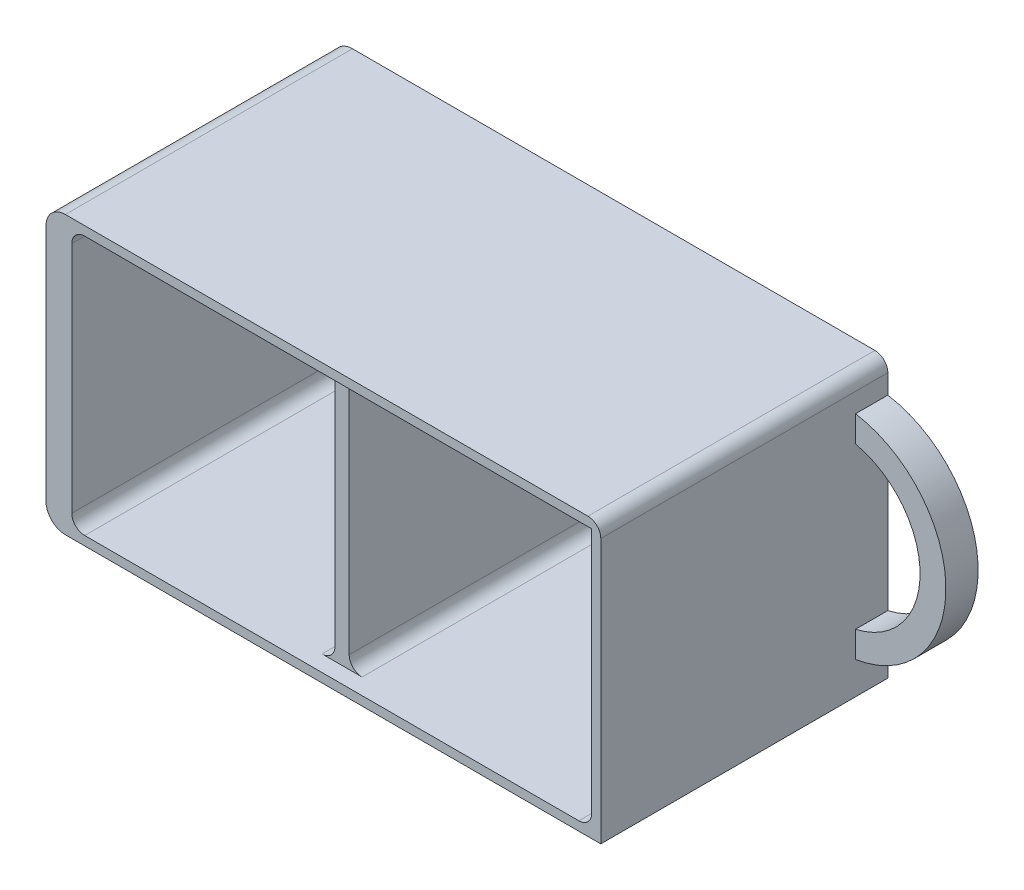
SolidWorks part; units mm, degrees
ref_plane "Спереди" through (0, 0, 0) normal (0, 0, 1) x (1, 0, 0)
ref_plane "Сверху" through (0, 0, 0) normal (0, 1, 0) x (1, 0, 0)
ref_plane "Справа" through (0, 0, 0) normal (1, 0, 0) x (0, 0, -1)
ref_plane "Плоскость4" through (0, 0, 22.25) normal (0, 0, 1) x (1, 0, 0)
sketch "Эскиз1" plane through (0, 0, 22.25) normal (0, 0, 1) x (1, 0, 0)
  line L0 (90, -21.5) -> (90, 21.5)
  line L1 (90, 21.5) -> (4, 21.5)
  line L2 (4, 21.5) -> (4, -21.5)
  line L3 (4, -21.5) -> (90, -21.5)
extrude "Бобышка-Вытянуть1" add sketch "Эскиз1" against normal blind 39.5
sketch "Эскиз2" plane through (0, 0, -17.25) normal (0, 0, -1) x (-1, 0, 0)
  line L0 (-90, -21.5) -> (-90, -16.5)
  line L1 (-90, 16.5) -> (-90, 21.5)
  line L2 (-90, 21.5) -> (-4, 21.5)
  line L3 (-4, 21.5) -> (-4, -21.5)
  line L4 (-4, -21.5) -> (-90, -21.5)
  line L5 (-90, -12.4284) -> (-90, 12.4284)
  arc A0 (-90, -16.5) -> (-90, 16.5) centre (-87.2768, 0) cw
  arc A1 (-90, 12.4284) -> (-90, -12.4284) centre (-87.2768, 0) ccw
extrude "Бобышка-Вытянуть2" add sketch "Эскиз2" along normal blind 5
sketch "Эскиз3" plane through (0, 0, 22.25) normal (0, 0, 1) x (1, 0, 0)
  line L0 (88.6, -20.1) -> (88.6, 20.1)
  line L1 (88.6, 20.1) -> (8, 20.1)
  line L2 (8, 20.1) -> (8, -20.1)
  line L3 (8, -20.1) -> (88.6, -20.1)
extrude "Вырез-Вытянуть1" cut sketch "Эскиз3" against normal blind 43.6
hole_wizard "Диаметр отверстия Ø8.3 (8.3)1" positions "Эскиз5" profile "Эскиз4" hole size "Ø8.3" standard "Ansi Metric"
sketch "Эскиз5" plane through (4, 0, 0) normal (-1, 0, 0) x (0, 0, 1)
  point P0 (0, 0)
sketch "Эскиз4" plane through (4, 0, 0) normal (0, 1, 0) x (0, 0, 1)
  line L0 (0, 0) -> (0, 3.2)
  line L1 (0, 3.2) -> (4.15, 3.2)
  line L2 (4.15, 3.2) -> (4.15, 0)
  line L5 (4.15, 0) -> (0, 0)
  line L10 (0, 3.2) -> (-4.15, 3.2) construction
  line L11 (0, -6.35) -> (0, 107.95) construction
  dimension "Диаметр отверстия" = 8.3
  dimension "Глубина отверстия" = 3.2
  dimension "Угол заточки сверла" = 180
fillet "Скругление1" radius 3 2 edges at (4, -21.5, 0) (4, 21.5, 0)
sketch "Эскиз6" plane through (4, 0, 0) normal (-1, 0, 0) x (0, 0, 1)
  circle A0 centre (0, 0) radius 4.15 construction
  circle A1 centre (0, 0) radius 4.15
extrude "Бобышка-Вытянуть3" add sketch "Эскиз6" against normal blind 4
sketch "Эскиз10" plane through (0, 0, -22.25) normal (0, 0, -1) x (-1, 0, 0)
  line L0 (-47.4, 30.6908) -> (-47.4, -26.5541) construction
  line L2 (0, 0) -> (-118.0019, 0) construction
  line L3 (-90, -21.5) -> (-7, -21.5) construction
  line L4 (-48.5, 21.5) -> (-46.3, 21.5)
  line L5 (-48.5, 21.5) -> (-48.5, -21.5)
  line L6 (-48.5, -21.5) -> (-46.3, -21.5)
  line L7 (-46.3, 21.5) -> (-46.3, -21.5)
  line L8 (-48.5, 21.5) -> (-46.3, -21.5) construction
  line L9 (-48.5, -21.5) -> (-46.3, 21.5) construction
  point P4 (-47.4, 0)
  dimension "D1" = 42.6
  dimension "D2" = 18.5
  dimension "D3" = 2.2
extrude "Бобышка-Вытянуть5" add sketch "Эскиз10" against normal blind 42
fillet "Скругление2" radius 2 16 edges at (27.15, -20.1, -21.35) (8, 0, -21.35) (27.15, 20.1, -21.35) (46.3, 0, -21.35) (68.55, 20.1, -21.35) (88.6, 0, -21.35) (68.55, -20.1, -21.35) (48.5, 0, -21.35) (90, 21.5, 0) (48.5, 20.1, -0.8) (46.3, 20.1, -0.8) (8, 20.1, 0.45) (8, -20.1, 0.45) (46.3, -20.1, -0.8) (48.5, -20.1, -0.8) (88.6, -20.1, 0.45)
